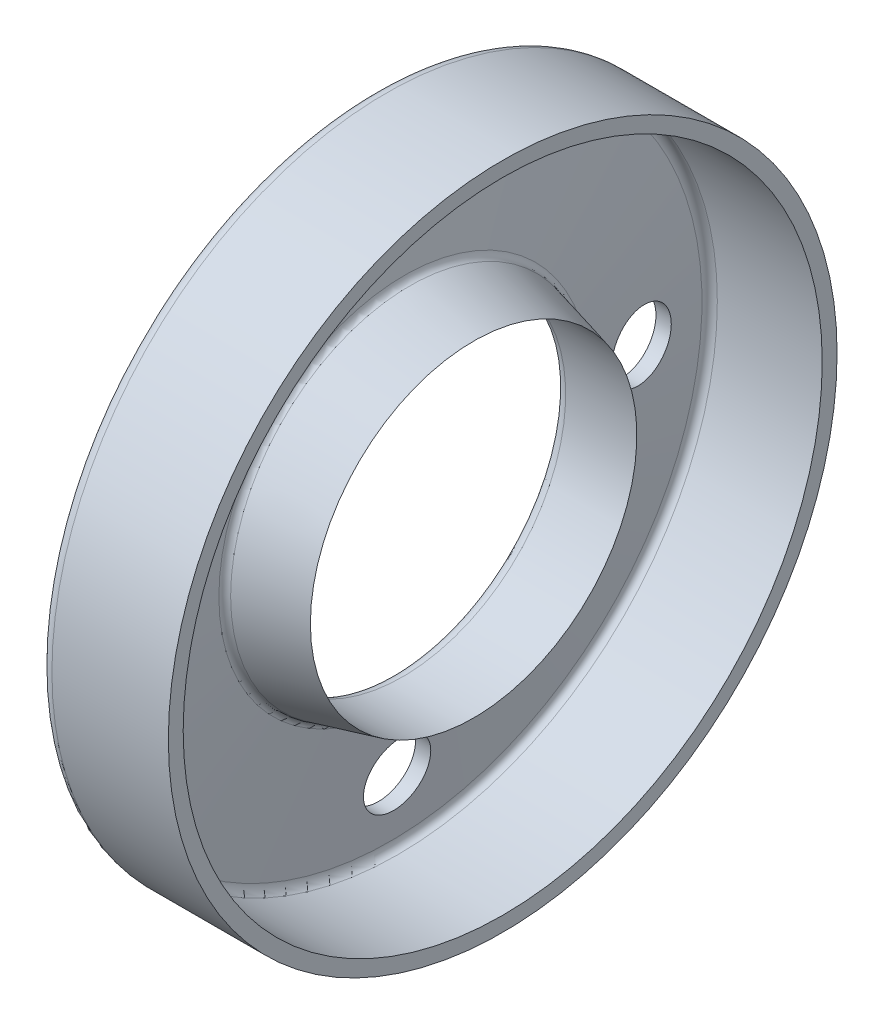
SolidWorks part; units mm, degrees
ref_plane "Front Plane" through (0, 0, 0) normal (0, 0, 1) x (1, 0, 0)
ref_plane "Top Plane" through (0, 0, 0) normal (0, 1, 0) x (1, 0, 0)
ref_plane "Right Plane" through (0, 0, 0) normal (1, 0, 0) x (0, 0, -1)
sketch "Sketch1" plane through (0, 0, 0) normal (0, 0, 1) x (1, 0, 0)
  line L0 (0.1553, 33.4777) -> (1.8438, 18.1615)
  line L1 (3.1062, 17.0307) -> (10.5283, 17.0307)
  line L2 (10.5283, 17.0307) -> (3.8801, 18.7048)
  line L3 (3.3088, 19.3603) -> (1.8611, 32.492)
  line L4 (2.6185, 33.3375) -> (13.5636, 33.3375)
  line L5 (13.5636, 33.3375) -> (13.5636, 34.8869)
  line L6 (13.5636, 34.8869) -> (1.4177, 34.8869)
  line L7 (-1000.5387, 0) -> (48999.4613, 0) construction
  arc A0 (1.8611, 32.492) -> (2.6185, 33.3375) centre (2.6185, 32.5755) cw
  arc A1 (3.8801, 18.7048) -> (3.3088, 19.3603) centre (4.0662, 19.4438) cw
  arc A2 (1.8438, 18.1615) -> (3.1062, 17.0307) centre (3.1062, 18.3007) ccw
  arc A3 (0.1553, 33.4777) -> (1.4177, 34.8869) centre (1.4177, 33.6169) cw
  point P12 (3.3668, 18.8341)
  point P15 (1.9685, 17.0307)
  point P18 (0, 34.8869)
  dimension "D9" = 0.762
  dimension "D10" = 1.27
  dimension "D1" = 34.8869
  dimension "D2" = 13.5636
  dimension "D3" = 1.5494
  dimension "D4" = 1.5875
  dimension "D5" = 17.0307
  dimension "D6" = 18.8341
  dimension "D7" = 10.5283
  dimension "D8" = 8.5598
revolve "Revolve1" add sketch "Sketch1" angle 360 about L7
sketch "Sketch2" plane through (0, 0, 0) normal (1, 0, 0) x (0, 0, -1)
  line L0 (-1000, 0) -> (49000, 0) construction
  circle A0 centre (0, -26.0604) radius 3.4925
  circle A1 centre (0, 26.0604) radius 3.4925
  circle A2 centre (25.4, 0) radius 3.4925
  dimension "D3" = 25.4
  dimension "D1" = 26.0604
  dimension "D2" = 6.985
  dimension "D4" = 6.985
extrude "Cut-Extrude1" cut sketch "Sketch2" along normal through all
